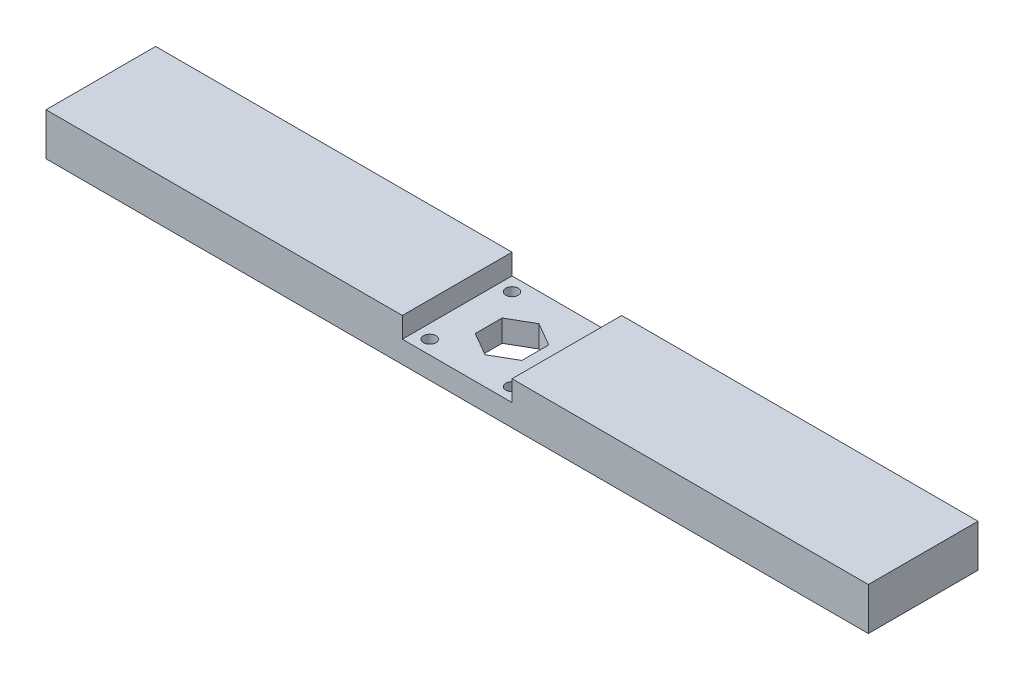
SolidWorks part; units mm, degrees
ref_plane "Front Plane" through (0, 0, 0) normal (0, 0, 1) x (1, 0, 0)
ref_plane "Top Plane" through (0, 0, 0) normal (0, 1, 0) x (1, 0, 0)
ref_plane "Right Plane" through (0, 0, 0) normal (1, 0, 0) x (0, 0, -1)
sketch "Sketch1" plane through (0, 0, 0) normal (0, 0, 1) x (1, 0, 0)
  line L0 (0, 104.1848) -> (0, -100.9565) construction
  line L1 (-150, 7.75) -> (-150, -7.75)
  line L2 (-150, -7.75) -> (150, -7.75)
  line L3 (-150, 7.75) -> (-20, 7.75)
  line L4 (-20, 7.75) -> (-20, 0.25)
  line L5 (-20, 0.25) -> (20, 0.25)
  line L6 (150, 7.75) -> (150, -7.75)
  line L7 (20, 7.75) -> (20, 0.25)
  line L8 (150, 7.75) -> (20, 7.75)
  point P5 (-150, 0)
  point P12 (0, -7.75)
  point P14 (0, 0.25)
  dimension "D1" = 300
  dimension "D2" = 15.5
  dimension "D3" = 7.5
  dimension "D4" = 40
extrude "Boss-Extrude1" add sketch "Sketch1" along normal mid plane 40
sketch "Sketch2" plane through (0, 0.25, 0) normal (0, 1, 0) x (1, 0, 0)
  line L0 (-3.5, 3.5) -> (-1.225, 3.5) construction
  line L1 (-3.5, 10) -> (3.5, 10) construction
  line L2 (-3.5, 10) -> (-3.5, 3.5) construction
  line L3 (-3.5, -10) -> (3.5, -10) construction
  line L4 (3.5, 10) -> (3.5, 3.5) construction
  line L5 (-3.5, 10) -> (3.5, -10) construction
  line L6 (-3.5, -10) -> (3.5, 10) construction
  line L7 (-10, 3.5) -> (-3.5, 3.5) construction
  line L8 (-10, 3.5) -> (-10, -3.5) construction
  line L9 (-10, -3.5) -> (-3.5, -3.5) construction
  line L10 (10, 3.5) -> (10, -3.5) construction
  line L11 (-10, 3.5) -> (10, -3.5) construction
  line L12 (-10, -3.5) -> (10, 3.5) construction
  line L13 (-1.225, 3.5) -> (1.225, 3.5) construction
  line L14 (-3.5, 3.5) -> (-3.5, 1.225) construction
  line L15 (-3.5, -3.5) -> (-3.5, -10) construction
  line L16 (-3.5, 1.225) -> (-3.5, -1.225) construction
  line L17 (-3.5, -1.225) -> (-3.5, -3.5) construction
  line L18 (-3.5, -3.5) -> (-1.225, -3.5) construction
  line L19 (3.5, -3.5) -> (10, -3.5) construction
  line L20 (-1.225, -3.5) -> (1.225, -3.5) construction
  line L21 (1.225, -3.5) -> (3.5, -3.5) construction
  line L22 (3.5, -1.225) -> (3.5, -3.5) construction
  line L23 (3.5, -3.5) -> (3.5, -10) construction
  line L24 (3.5, 1.225) -> (3.5, -1.225) construction
  line L25 (3.5, 3.5) -> (3.5, 1.225) construction
  line L26 (1.225, 3.5) -> (3.5, 3.5) construction
  line L27 (3.5, 3.5) -> (10, 3.5) construction
  line L28 (0, 16.757) -> (0, -13.5066) construction
  line L29 (-13.5311, 0) -> (11.9505, 0) construction
  line L31 (0, -9.815) -> (8.5, -4.9075)
  line L32 (8.5, -4.9075) -> (8.5, 4.9075)
  line L33 (8.5, 4.9075) -> (0, 9.815)
  line L34 (0, 9.815) -> (-8.5, 4.9075)
  line L35 (-8.5, 4.9075) -> (-8.5, -4.9075)
  line L36 (-8.5, -4.9075) -> (0, -9.815)
  circle A0 centre (15, 15) radius 2.25
  circle A1 centre (-15, 15) radius 2.25
  circle A2 centre (15, -15) radius 2.25
  circle A3 centre (-15, -15) radius 2.25
  circle A4 centre (0, 0) radius 8.5 construction
  point P0 (0, 0)
  point P5 (0, 0)
  dimension "D5" = 15
  dimension "D7" = 4.5
  dimension "D1" = 7
  dimension "D2" = 20
  dimension "D3" = 7
  dimension "D4" = 20
  dimension "D6" = 15
  dimension "D8" = 17
extrude "Cut-Extrude1" cut sketch "Sketch2" against normal blind 40
